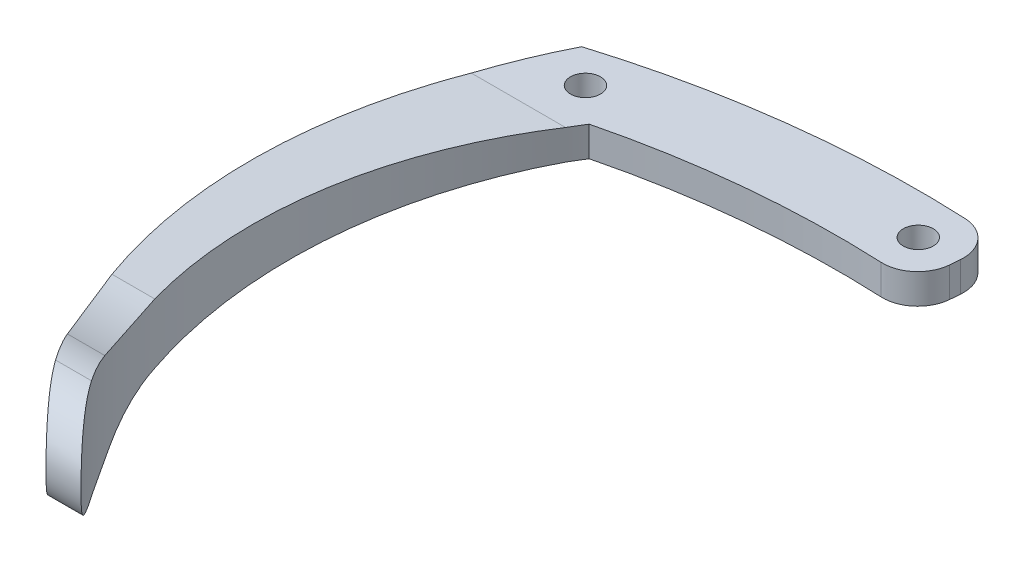
SolidWorks part; units mm, degrees
ref_plane "Front Plane" through (0, 0, 0) normal (0, 0, 1) x (1, 0, 0)
ref_plane "Top Plane" through (0, 0, 0) normal (0, 1, 0) x (1, 0, 0)
ref_plane "Right Plane" through (0, 0, 0) normal (1, 0, 0) x (0, 0, -1)
sketch "Sketch1" plane through (0, 0, 0) normal (0, 1, 0) x (1, 0, 0)
  line L0 (0, 0) -> (8.3741, -61.9364) construction
  line L5 (0, 0) -> (37.3284, 0) construction
  line L6 (8.3741, -61.9364) -> (11.8741, -61.9364)
  line L8 (37.3702, 0.4986) -> (37.2867, -0.4986)
  line L9 (0, 0) -> (7.0813, -6.3328) construction
  line L10 (33.5051, 4.3106) -> (33.1711, -3.6824) construction
  line L11 (3.5407, -3.1664) -> (33.3381, 0.3141) construction
  arc A0 (0, 0) -> (8.3741, -61.9364) centre (49.0386, -24.9041) ccw
  arc A2 (0, 0) -> (34.0475, 4.2865) centre (29.3297, -95.6021) cw
  arc A4 (33.6351, -3.7029) -> (7.0813, -6.3328) centre (29.3297, -95.6021) ccw
  arc A5 (11.8741, -61.9364) -> (7.0813, -6.3328) centre (45.912, -30.9942) cw
  circle A6 centre (3.5407, -3.1664) radius 1.5
  circle A7 centre (33.3381, 0.3141) radius 1.5
  arc A8 (34.0475, 4.2865) -> (37.3702, 0.4986) centre (33.8823, 0.7904) cw
  arc A9 (37.2867, -0.4986) -> (33.6351, -3.7029) centre (33.7989, -0.2068) cw
  point P12 (37.3284, 0)
  point P14 (37.3284, 0)
  point P16 (3.5407, -3.1664)
  point P24 (37.6673, 4.0497)
  point P27 (37.0003, -3.9225)
  dimension "D5" = 55
  dimension "D7" = 9.5
  dimension "D9" = 100
  dimension "D10" = 3
  dimension "D2" = 46
  dimension "D11" = 4
  dimension "D12" = 3
  dimension "D13" = 3.5
  dimension "D1" = 8
  dimension "D3" = 82.3
  dimension "D4" = 62.5
  dimension "D6" = 3.5
  dimension "D8" = 30
extrude "Boss-Extrude1" add sketch "Sketch1" along normal blind 10
sketch "Sketch3" plane through (0, 0, 0) normal (1, 0, 0) x (0, 0, -1)
  line L0 (-56.9364, 10) -> (-56.9364, 0) construction
  line L1 (-6.3328, 10) -> (-61.9364, 10) construction
  line L2 (-61.9364, 0) -> (-6.3328, 0) construction
  line L3 (-61.9364, 10) -> (-61.9364, 0) construction
  line L9 (4.3979, 0) -> (4.3979, 10) construction
  line L10 (12.084, 3.5) -> (12.084, -15.2222)
  line L11 (12.084, 24.1239) -> (-68.4887, 24.1239)
  line L12 (12.084, 24.1239) -> (12.084, 6.5)
  line L13 (12.084, -15.2222) -> (-68.4887, -15.2222)
  line L14 (-68.4887, 24.1239) -> (-68.4887, -15.2222)
  line L15 (-7.8021, 6.5) -> (12.084, 6.5)
  line L17 (-7.8021, 3.5) -> (12.084, 3.5)
  line L19 (-44.6864, 8) -> (-7.8021, 6.5)
  line L20 (-44.6864, 2) -> (-7.8021, 3.5)
  line L21 (-7.8021, 6.5) -> (-7.8021, 10) construction
  line L22 (-7.8021, 3.5) -> (-7.8021, 0) construction
  line L23 (-44.6864, 8) -> (-44.6864, 10) construction
  line L24 (-44.6864, 2) -> (-44.6864, 0) construction
  arc A0 (-52.6813, 0.5909) -> (-44.6864, 2) centre (-44.4022, -22.9984) cw
  arc A1 (-53.4364, 9.3542) -> (-44.6864, 8) centre (-45.2981, 32.9925) ccw
  ellipse E0 centre (-56.9364, 5) end of major axis (-56.9364, 0) minor radius 5 (-56.9364, 10) -> (-56.9364, 0) ccw
  ellipse E1 centre (-56.9364, 5) end of major axis (-48.9364, 4.466) minor radius 4.9932 (-56.9364, 0) -> (-52.6813, 0.5909) ccw
  ellipse E2 centre (-56.9364, 5) end of major axis (-48.9364, 4.466) minor radius 4.9932 (-53.4364, 9.3542) -> (-56.9364, 10) ccw
  dimension "D5" = 25
  dimension "D1" = 5
  dimension "D2" = 12.2
  dimension "D3" = 6
  dimension "D4" = 8
  dimension "D6" = 12.25
  dimension "D7" = 3
  dimension "D8" = 3.5
extrude "Cut-Extrude2" cut sketch "Sketch3" against normal through all and the other way through all
